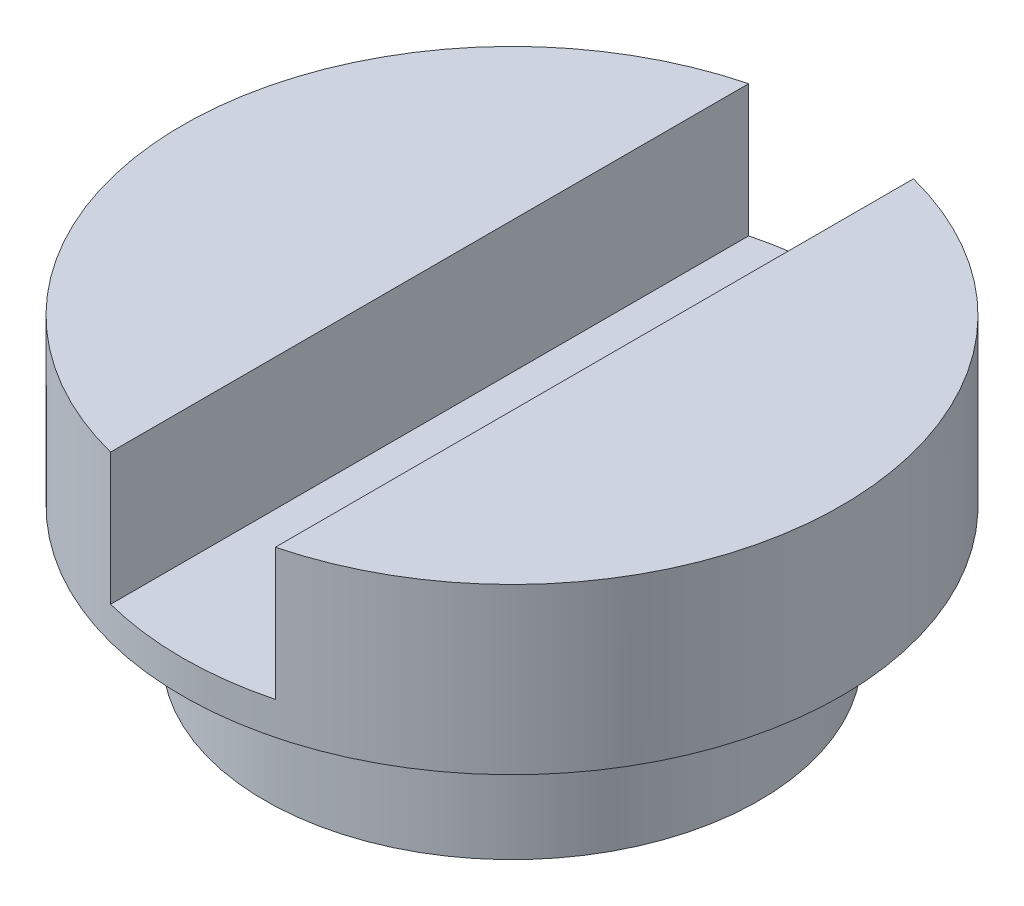
SolidWorks part; units mm, degrees
ref_plane "Front Plane" through (0, 0, 0) normal (0, 0, 1) x (1, 0, 0)
ref_plane "Top Plane" through (0, 0, 0) normal (0, 1, 0) x (1, 0, 0)
ref_plane "Right Plane" through (0, 0, 0) normal (1, 0, 0) x (0, 0, -1)
sketch "Sketch1" plane through (0, 243.3466, 0) normal (0, -1, 0) x (1, 0, 0)
  arc A0 (170.9764, 548.7463) -> (170.9764, 524.1529) centre (174.1514, 536.4496) ccw construction
  arc A1 (170.9764, 524.1529) -> (177.3264, 524.1529) centre (174.1514, 536.4496) ccw construction
  arc A2 (177.3264, 524.1529) -> (177.3264, 548.7463) centre (174.1514, 536.4496) ccw construction
  arc A3 (177.3264, 548.7463) -> (170.9764, 548.7463) centre (174.1514, 536.4496) ccw construction
  arc A4 (170.9764, 548.7463) -> (170.9764, 524.1529) centre (174.1514, 536.4496) ccw
  arc A5 (170.9764, 524.1529) -> (177.3264, 524.1529) centre (174.1514, 536.4496) ccw
  arc A6 (177.3264, 524.1529) -> (177.3264, 548.7463) centre (174.1514, 536.4496) ccw
  arc A7 (177.3264, 548.7463) -> (170.9764, 548.7463) centre (174.1514, 536.4496) ccw
extrude "Boss-Extrude1" add sketch "Sketch1" along normal blind 1.27
sketch "Sketch2" plane through (0, 243.3466, 0) normal (0, 1, 0) x (1, 0, 0)
  line L0 (177.3264, -524.1529) -> (177.3264, -548.7463) construction
  line L1 (177.3264, -524.1529) -> (177.3264, -548.7463)
  line L2 (170.9764, -548.7463) -> (170.9764, -524.1529) construction
  line L3 (170.9764, -548.7463) -> (170.9764, -524.1529)
  arc A0 (177.3264, -548.7463) -> (177.3264, -524.1529) centre (174.1514, -536.4496) ccw
  circle A1 centre (174.1514, -536.4496) radius 12.7
  arc A2 (170.9764, -524.1529) -> (170.9764, -548.7463) centre (174.1514, -536.4496) ccw
  dimension "D1" = 0
extrude "Boss-Extrude2" add sketch "Sketch2" along normal up to surface (5.08 mm away)
sketch "Sketch3" plane through (0, 242.0766, 0) normal (0, -1, 0) x (1, 0, 0)
  circle A0 centre (174.1514, 536.4496) radius 9.525 construction
  circle A1 centre (174.1514, 536.4496) radius 9.525
extrude "Boss-Extrude3" add sketch "Sketch3" along normal blind 5.08
sketch "Sketch7" plane through (0, 236.9966, 0) normal (0, -1, 0) x (1, 0, 0)
  circle A0 centre (174.1514, 536.4496) radius 2.85 construction
  circle A1 centre (174.1514, 536.4496) radius 2.85
extrude "Cut-Extrude2" cut sketch "Sketch7" against normal up to surface (4.85 mm away)
